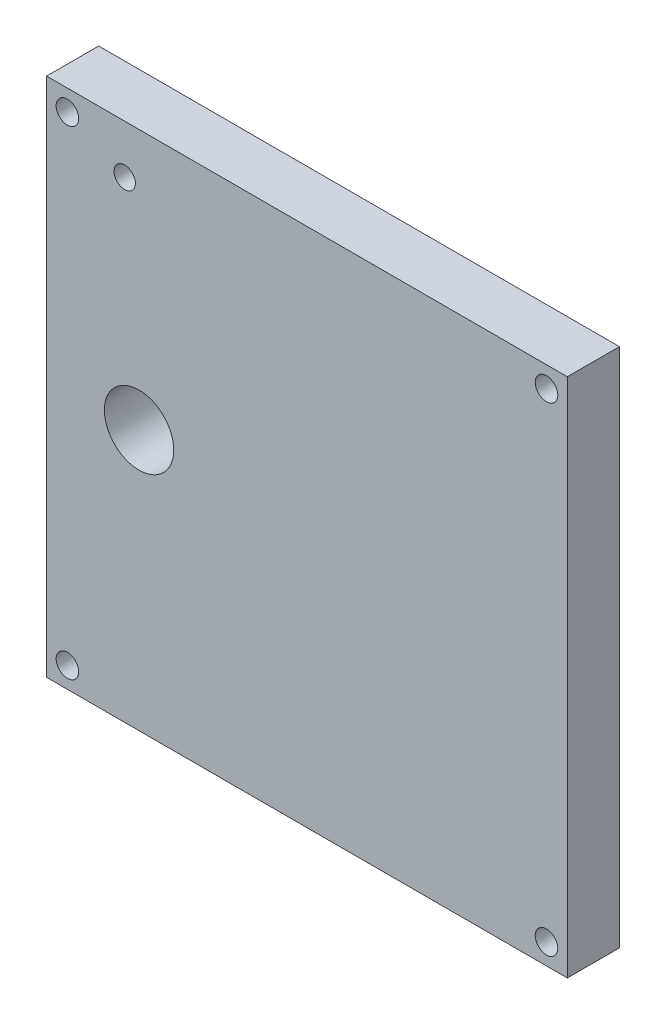
SolidWorks part; units mm, degrees
ref_plane "Front Plane" through (0, 0, 0) normal (0, 0, 1) x (1, 0, 0)
ref_plane "Top Plane" through (0, 0, 0) normal (0, 1, 0) x (1, 0, 0)
ref_plane "Right Plane" through (0, 0, 0) normal (1, 0, 0) x (0, 0, -1)
sketch "Sketch1" plane through (0, 0, 0) normal (0, 0, 1) x (1, 0, 0)
  line L1 (-75, 75) -> (75, 75)
  line L2 (-75, 75) -> (-75, -75)
  line L3 (-75, -75) -> (75, -75)
  line L4 (75, 75) -> (75, -75)
  line L5 (-75, 75) -> (75, -75) construction
  line L6 (-75, -75) -> (75, 75) construction
  point P0 (0, 0)
  dimension "D1" = 150
  dimension "D2" = 150
extrude "Boss-Extrude1" add sketch "Sketch1" along normal mid plane 15
sketch "Sketch2" plane through (0, 0, -7.5) normal (0, 0, -1) x (-1, 0, 0)
  line L4 (-75, 75) -> (-75, -75)
  line L5 (-75, -75) -> (75, -75)
  line L6 (75, -75) -> (75, 75)
  line L7 (75, 75) -> (-75, 75)
  line L8 (-75, 75) -> (-75, -75)
  line L9 (-75, -75) -> (75, -75)
  line L10 (75, -75) -> (75, 75)
  line L11 (75, 75) -> (-75, 75)
  circle A0 centre (52.5, 61) radius 3.075 construction
  circle A1 centre (52.5, 61) radius 3.075
  dimension "D1" = 0
extrude "Cut-Extrude2" cut sketch "Sketch2" against normal blind 32 contours A1
sketch "Sketch3" plane through (0, 0, -7.5) normal (0, 0, -1) x (-1, 0, 0)
  circle A0 centre (-21.0575, 23.2633) radius 3.5
  circle A1 centre (-58.9425, -23.2633) radius 3.5
sketch "Sketch4" plane through (0, 0, 7.5) normal (0, 0, 1) x (1, 0, 0)
  circle A0 centre (3.95, 46.1) radius 1.5
  circle A1 centre (-18, 46.1) radius 1.5
  circle A2 centre (-18, 1.9) radius 1.5
  circle A3 centre (3.95, 1.9) radius 1.5
extrude "Cut-Extrude4" [suppressed] cut sketch "Sketch4" against normal blind 22
sketch "Sketch5" plane through (0, 0, 7.5) normal (0, 0, 1) x (1, 0, 0)
  line L0 (-48.3691, 75) -> (-48.3691, -75) construction
  line L1 (75, 75) -> (-75, 75) construction
  line L2 (-75, -75) -> (75, -75) construction
  circle A0 centre (-48.3691, 0) radius 10
  dimension "D1" = 20
extrude "Cut-Extrude5" cut sketch "Sketch5" against normal blind 22
sketch "Sketch6" plane through (0, 0, -7.5) normal (0, 0, -1) x (-1, 0, 0)
  line L0 (-75, 75) -> (75, 75) construction
  line L1 (75, 75) -> (75, -75) construction
  circle A0 centre (69, 69) radius 3.25
  dimension "D1" = 6.5
  dimension "D2" = 6
  dimension "D3" = 6
extrude "Cut-Extrude6" cut sketch "Sketch6" against normal blind 22
mirror "Mirror1" about plane through (0, 0, 0) normal (0, 1, 0) of "Cut-Extrude6"
mirror "Mirror2" about plane through (0, 0, 0) normal (1, 0, 0) of "Mirror1", "Cut-Extrude6"
